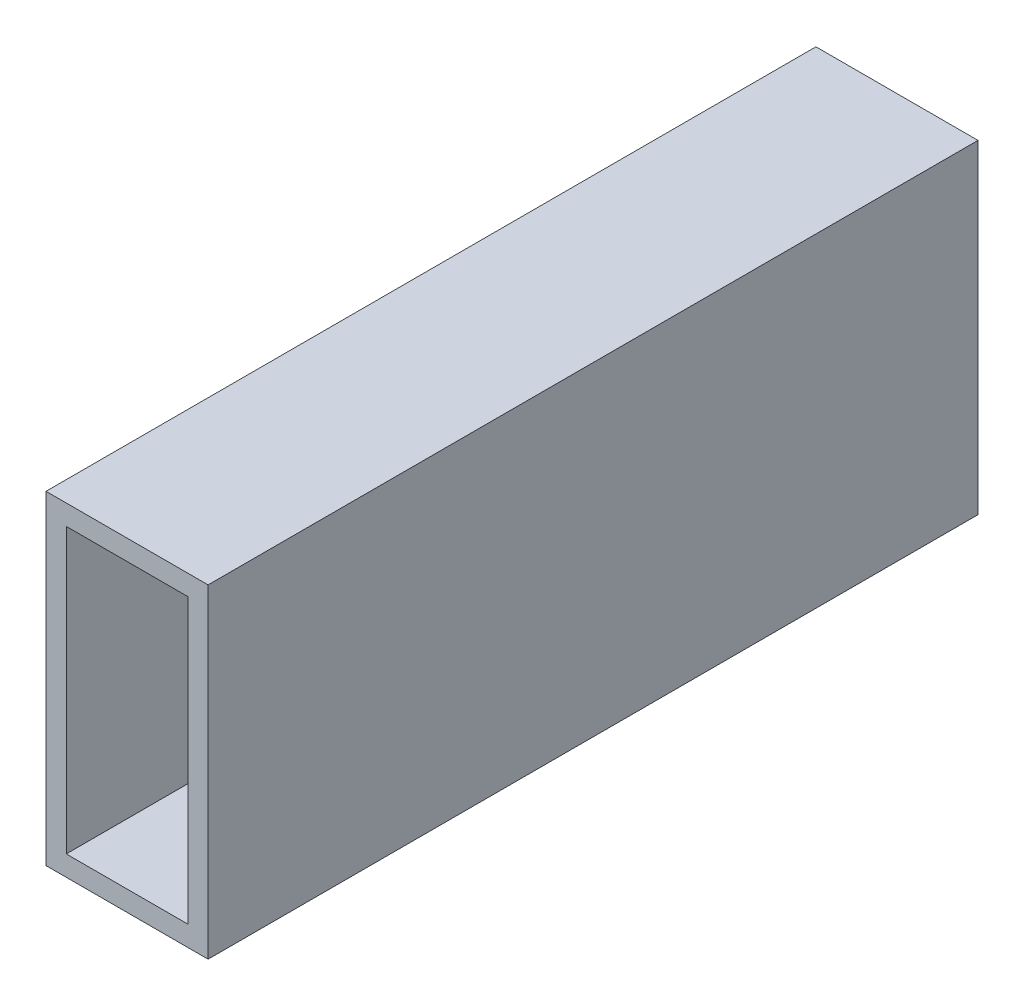
SolidWorks part; units mm, degrees
ref_plane "Front Plane" through (0, 0, 0) normal (0, 0, 1) x (1, 0, 0)
ref_plane "Top Plane" through (0, 0, 0) normal (0, 1, 0) x (1, 0, 0)
ref_plane "Right Plane" through (0, 0, 0) normal (1, 0, 0) x (0, 0, -1)
sketch "Sketch1" plane through (0, 0, 0) normal (0, 0, 1) x (1, 0, 0)
  line L0 (22.225, 3.175) -> (22.225, 47.625)
  line L1 (0, 0) -> (25.4, 0)
  line L2 (0, 0) -> (0, 50.8)
  line L3 (0, 50.8) -> (25.4, 50.8)
  line L4 (25.4, 0) -> (25.4, 50.8)
  line L5 (3.175, 47.625) -> (22.225, 47.625)
  line L6 (3.175, 3.175) -> (3.175, 47.625)
  line L7 (3.175, 3.175) -> (22.225, 3.175)
  dimension "D1" = 50.8
  dimension "D2" = 25.4
  dimension "D3" = 3.175
extrude "Boss-Extrude1" add sketch "Sketch1" along normal blind 120.65
